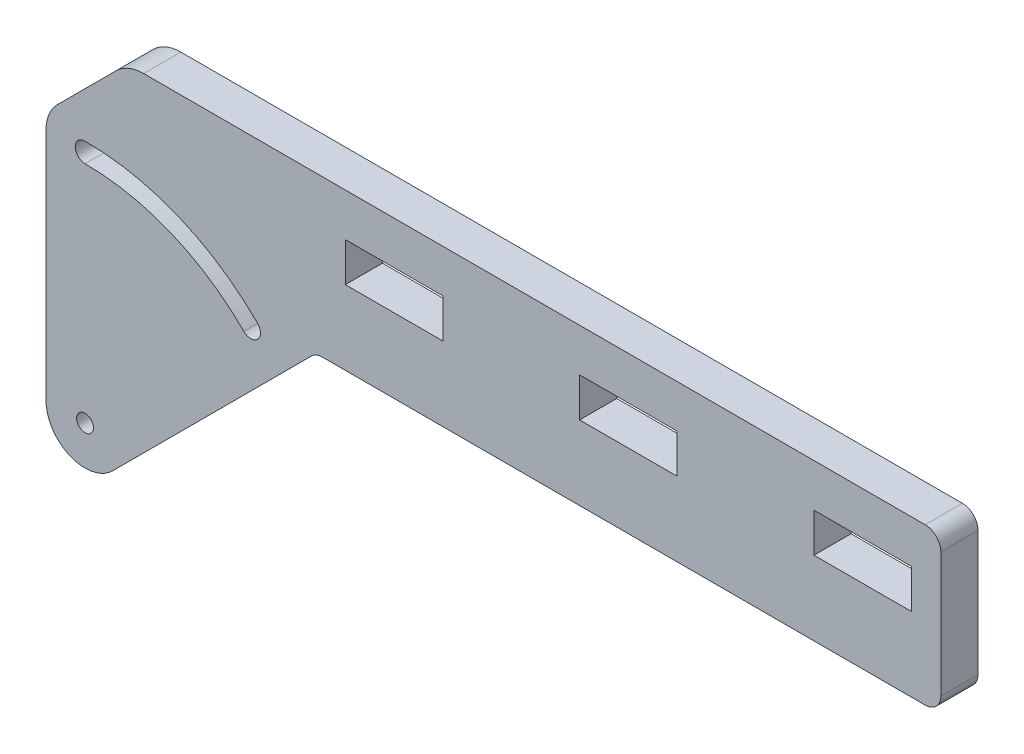
SolidWorks part; units mm, degrees
ref_plane "Front Plane" through (0, 0, 0) normal (0, 0, 1) x (1, 0, 0)
ref_plane "Top Plane" through (0, 0, 0) normal (0, 1, 0) x (1, 0, 0)
ref_plane "Right Plane" through (0, 0, 0) normal (1, 0, 0) x (0, 0, -1)
sketch "Sketch1" plane through (0, 0, 0) normal (0, 0, 1) x (1, 0, 0)
  line L0 (0, 0) -> (26.9408, 26.9408) construction
  line L1 (0, 0) -> (0, 38.1) construction
  line L2 (-6.35, 38.1) -> (-6.35, 0)
  line L3 (4.4901, -4.4901) -> (31.4309, 22.4506)
  line L4 (0, 0) -> (37.5553, 0) construction
  line L5 (37.5553, 0) -> (37.5553, 28.575) construction
  line L6 (36.8113, 27.8311) -> (31.4309, 22.4506)
  line L7 (38.6074, 28.575) -> (136.6153, 28.575)
  line L10 (139.1553, 31.115) -> (139.1553, 51.435)
  line L12 (136.6153, 53.975) -> (9.525, 53.975)
  line L13 (-4.4901, 42.5901) -> (5.0349, 52.1151)
  circle A0 centre (0, 0) radius 1.3716
  arc A1 (-6.35, 0) -> (4.4901, -4.4901) centre (0, 0) ccw
  circle A2 centre (0, 0) radius 38.1 construction
  arc A3 (25.8182, 25.8182) -> (0, 36.5125) centre (0, 0) ccw
  arc A4 (28.0633, 28.0633) -> (0, 39.6875) centre (0, 0) ccw
  arc A5 (25.8182, 25.8182) -> (28.0633, 28.0633) centre (26.9408, 26.9408) ccw
  arc A6 (0, 39.6875) -> (0, 36.5125) centre (0, 38.1) ccw
  circle A9 centre (0, 0) radius 31.75 construction
  arc A10 (31.4309, 31.4309) -> (0, 44.45) centre (0, 0) ccw construction
  arc A12 (31.0411, 22.0921) -> (31.4309, 31.4309) centre (26.9408, 26.9408) ccw construction
  circle A13 centre (0, 38.1) radius 6.35 construction
  arc A14 (0, 44.45) -> (31.4309, 31.4309) centre (0, 0) ccw construction
  arc A15 (38.6074, 28.575) -> (36.8113, 27.8311) centre (38.6074, 26.035) ccw
  arc A16 (136.6153, 28.575) -> (139.1553, 31.115) centre (136.6153, 31.115) ccw
  arc A17 (-6.35, 38.1) -> (-4.4901, 42.5901) centre (0, 38.1) cw
  arc A18 (5.0349, 52.1151) -> (9.525, 53.975) centre (9.525, 47.625) cw
  arc A19 (139.1553, 51.435) -> (136.6153, 53.975) centre (136.6153, 51.435) ccw
  point P3 (8.9803, 0)
  point P12 (26.4872, 17.5069)
  point P29 (-6.35, 31.1085)
  dimension "D1" = 2.7432
  dimension "D2" = 12.7
  dimension "D3" = 76.2
  dimension "D4" = 79.375
  dimension "D5" = 73.025
  dimension "D6" = 45
  dimension "D7" = 63.5
  dimension "D8" = 88.9
  dimension "D9" = 135
  dimension "D13" = 2.54
  dimension "D15" = 6.35
  dimension "D12" = 12.7
  dimension "D17" = 2.54
  dimension "D10" = 28.575
  dimension "D11" = 28.575
  dimension "D14" = 25.4
  dimension "D16" = 101.6
extrude "Boss-Extrude1" add sketch "Sketch1" along normal blind 6.0452
sketch "Sketch2" plane through (0, 0, 6.0452) normal (0, 0, 1) x (1, 0, 0)
  line L0 (38.6074, 28.575) -> (136.6153, 28.575) construction
  line L1 (118.5178, 46.99) -> (134.3928, 46.99)
  line L2 (118.5178, 46.99) -> (118.5178, 40.64)
  line L3 (118.5178, 40.64) -> (134.3928, 40.64)
  line L4 (134.3928, 46.99) -> (134.3928, 40.64)
  line L5 (139.1553, 31.115) -> (139.1553, 51.435) construction
  line L6 (80.4178, 46.99) -> (80.4178, 40.64)
  line L7 (80.4178, 46.99) -> (96.2928, 46.99)
  line L8 (96.2928, 46.99) -> (96.2928, 40.64)
  line L9 (80.4178, 40.64) -> (96.2928, 40.64)
  line L10 (42.3178, 46.99) -> (42.3178, 40.64)
  line L11 (42.3178, 46.99) -> (58.1928, 46.99)
  line L12 (58.1928, 46.99) -> (58.1928, 40.64)
  line L13 (42.3178, 40.64) -> (58.1928, 40.64)
  line L14 (118.5178, 46.99) -> (80.4178, 46.99) construction
  dimension "D1" = 15.875
  dimension "D2" = 6.35
  dimension "D3" = 12.065
  dimension "D4" = 4.7625
  dimension "D5" = 38.1
  dimension "D6" = 3
extrude "Cut-Extrude1" cut sketch "Sketch2" against normal blind 6.0452
